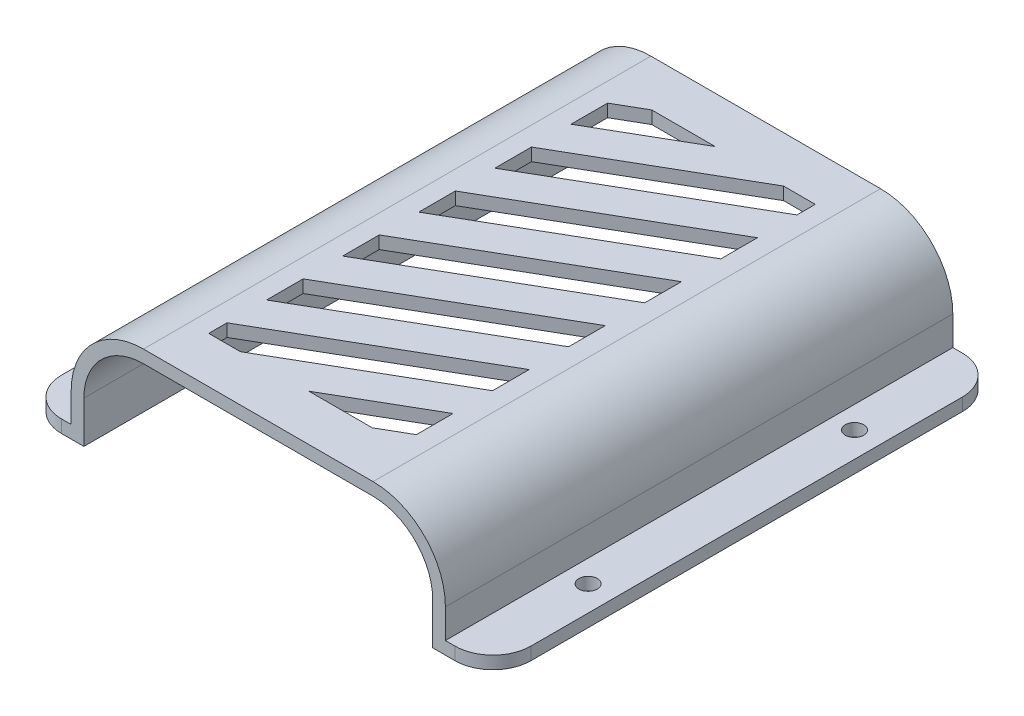
SolidWorks part; units mm, degrees
ref_plane "前视基准面" through (0, 0, 0) normal (0, 0, 1) x (1, 0, 0)
ref_plane "上视基准面" through (0, 0, 0) normal (0, 1, 0) x (1, 0, 0)
ref_plane "右视基准面" through (0, 0, 0) normal (1, 0, 0) x (0, 0, -1)
sketch "草图1" plane through (0, 0, 0) normal (0, 0, 1) x (1, 0, 0)
  line L0 (-37, 0) -> (-27.5, 0)
  line L1 (37, 0) -> (37, 2)
  line L2 (37, 2) -> (29.5, 2)
  line L3 (29.5, 2) -> (29.5, 6.6)
  line L4 (18.1, 18) -> (-18.1, 18)
  line L5 (-29.5, 6.6) -> (-29.5, 2)
  line L6 (-29.5, 2) -> (-37, 2)
  line L7 (-37, 2) -> (-37, 0)
  line L8 (-27.5, 0) -> (-27.5, 6.6)
  line L9 (-18.1, 16) -> (18.1, 16)
  line L10 (27.5, 6.6) -> (27.5, 0)
  line L11 (27.5, 0) -> (37, 0)
  arc A0 (29.5, 6.6) -> (18.1, 18) centre (18.1, 6.6) ccw
  arc A1 (-18.1, 18) -> (-29.5, 6.6) centre (-18.1, 6.6) ccw
  arc A2 (-27.5, 6.6) -> (-18.1, 16) centre (-18.1, 6.6) cw
  arc A3 (18.1, 16) -> (27.5, 6.6) centre (18.1, 6.6) cw
  dimension "D9" = 9.4
  dimension "D10" = 9.4
  dimension "D1" = 74
  dimension "D2" = 37
  dimension "D3" = 2
  dimension "D4" = 2
  dimension "D5" = 59
  dimension "D6" = 29.5
  dimension "D7" = 16
  dimension "D8" = 2
extrude "凸台-拉伸1" add sketch "草图1" along normal blind 80
sketch "草图2" plane through (0, 2, 0) normal (0, 1, 0) x (1, 0, 0)
  line L0 (-37, -40) -> (37, -40) construction
  line L1 (-37, -80) -> (-37, 0) construction
  line L2 (37, -80) -> (37, 0) construction
  line L3 (0, 0) -> (0, -80) construction
  line L4 (18.1, -80) -> (-18.1, -80) construction
  circle A0 centre (-33, -19) radius 1.45
  circle A1 centre (-33, -61) radius 1.45
  circle A2 centre (33, -61) radius 1.45
  circle A3 centre (33, -19) radius 1.45
  dimension "D1" = 2.9
  dimension "D2" = 33
  dimension "D3" = 21
extrude "切除-拉伸1" cut sketch "草图2" against normal blind 80
fillet "圆角1" radius 6 4 edges at (37, 1, 0) (-37, 1, 0) (-37, 1, 80) (37, 1, 80)
sketch "草图3" plane through (0, 18, 0) normal (0, 1, 0) x (1, 0, 0)
  line L4 (0.6846, -72.7182) -> (10.6846, -72.7182)
  line L5 (-15.1, -72.7182) -> (-10.1, -72.7182)
  line L6 (-15.1, -72.7182) -> (-15.1, -69.8315)
  line L27 (15.1, -70.169) -> (15.1, -64.3955)
  line L28 (15.1, -64.3955) -> (0.6846, -72.7182)
  line L30 (10.6846, -72.7182) -> (15.1, -70.169)
  line L31 (18.1, -80) -> (-18.1, -80) construction
  line L32 (-10.6846, -7.2822) -> (-0.6846, -7.2822)
  line L57 (15.1, -70.169) -> (15.1, -64.3955)
  line L58 (15.1, -58.169) -> (15.1, -52.3955)
  line L59 (15.1, -52.3955) -> (-15.1, -69.8315)
  line L60 (-15.1, -69.8315) -> (-15.1, -72.7182)
  line L61 (-10.1, -72.7182) -> (15.1, -58.169)
  line L62 (15.1, -46.169) -> (15.1, -40.3955)
  line L63 (15.1, -40.3955) -> (-15.1, -57.8315)
  line L64 (-15.1, -57.8315) -> (-15.1, -63.605)
  line L65 (-15.1, -63.605) -> (15.1, -46.169)
  line L66 (15.1, -34.169) -> (15.1, -28.3955)
  line L67 (15.1, -28.3955) -> (-15.1, -45.8315)
  line L68 (-15.1, -45.8315) -> (-15.1, -51.605)
  line L69 (-15.1, -51.605) -> (15.1, -34.169)
  line L70 (15.1, -22.169) -> (15.1, -16.3955)
  line L71 (15.1, -16.3955) -> (-15.1, -33.8315)
  line L72 (-15.1, -33.8315) -> (-15.1, -39.605)
  line L73 (-15.1, -39.605) -> (15.1, -22.169)
  line L74 (15.1, -10.169) -> (15.1, -7.2822)
  line L75 (10.1, -7.2822) -> (-15.1, -21.8315)
  line L76 (-15.1, -21.8315) -> (-15.1, -27.605)
  line L77 (-15.1, -27.605) -> (15.1, -10.169)
  line L79 (-10.6846, -7.2822) -> (-15.1, -9.8315)
  line L80 (-15.1, -9.8315) -> (-15.1, -15.605)
  line L81 (-15.1, -15.605) -> (-0.6846, -7.2822)
  line L82 (15.1, 1.831) -> (15.1, 7.6045) [skipped]
  line L83 (15.1, -58.169) -> (15.1, -52.3955)
  line L84 (15.1, -46.169) -> (15.1, -40.3955)
  line L85 (-15.1, -63.605) -> (-15.1, -57.8315)
  line L86 (-15.1, -51.605) -> (-15.1, -45.8315)
  line L87 (15.1, -34.169) -> (15.1, -28.3955)
  line L88 (15.1, -22.169) -> (15.1, -16.3955)
  line L89 (-15.1, -39.605) -> (-15.1, -33.8315)
  line L90 (-15.1, -27.605) -> (-15.1, -21.8315)
  line L91 (15.1, -10.169) -> (15.1, -7.2822)
  line L92 (10.1, -7.2822) -> (15.1, -7.2822)
  line L93 (-15.1, -15.605) -> (-15.1, -9.8315)
  dimension "D1" = 7
  dimension "D4" = 9.831
extrude "切除-拉伸2" cut sketch "草图3" against normal blind 10 contours L4 L30 L27 L28 | L5 L61 L58 L59 L6 | L64 L65 L62 L63 | L68 L69 L66 L67 | L72 L73 L70 L71 | L92 L75 L76 L77 L74 | L80 L81 L32 L79
